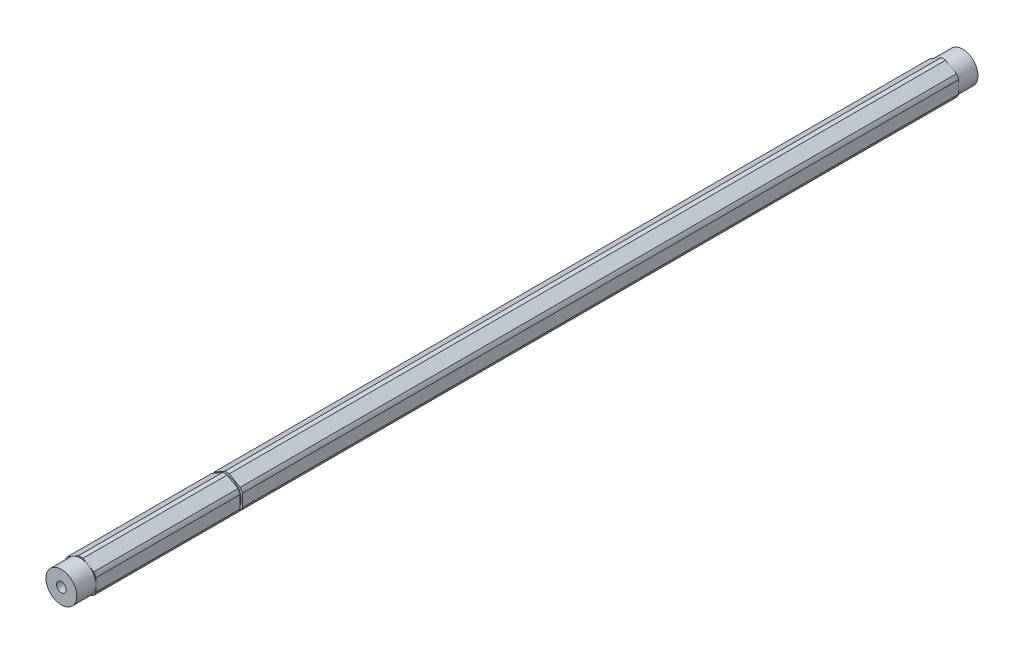
SolidWorks part; units mm, degrees
material "6061-T6 (SS)"
ref_plane "Front Plane" through (0, 0, 0) normal (0, 0, 1) x (1, 0, 0)
ref_plane "Top Plane" through (0, 0, 0) normal (0, 1, 0) x (1, 0, 0)
ref_plane "Right Plane" through (0, 0, 0) normal (1, 0, 0) x (0, 0, -1)
sketch "Sketch1" plane through (0, 0, 0) normal (0, 0, 1) x (1, 0, 0)
  line L1 (0, 7.3323) -> (-6.35, 3.6662)
  line L2 (-6.35, 3.6662) -> (-6.35, -3.6662)
  line L3 (-6.35, -3.6662) -> (0, -7.3323)
  line L4 (0, -7.3323) -> (6.35, -3.6662)
  line L5 (6.35, -3.6662) -> (6.35, 3.6662)
  line L6 (6.35, 3.6662) -> (0, 7.3323)
  circle A0 centre (0, 0) radius 6.35 construction
  circle A1 centre (0, 0) radius 2
  circle A2 centre (0, 0) radius 6.858
  dimension "D1" = 12.7
  dimension "D2" = 4
  dimension "D3" = 13.716
extrude "Boss-Extrude1" add sketch "Sketch1" along normal mid plane 355.6 contours L5 A2 L6 L1 L2 L3 L4 A1
sketch "Sketch3" plane through (0, 0, 177.8) normal (0, 0, 1) x (1, 0, 0)
  circle A0 centre (0, 0) radius 6.35
  circle A1 centre (0, 0) radius 2
  circle A2 centre (0, 0) radius 5.8547 construction
  point P5 (0, 5.8547)
  dimension "D1" = 12.7
  dimension "D2" = 4
  dimension "D3" = 11.7094
extrude "Boss-Extrude3" add sketch "Sketch3" along normal blind 7.9375
mirror "Mirror1" about plane through (0, 0, 0) normal (0, 0, 1) of "Boss-Extrude3"
sketch "Sketch5" plane through (0, 0, 0) normal (1, 0, 0) x (0, 0, -1)
  line L0 (-177.8, 5.8547) -> (-117.475, 5.8547) construction
  line L1 (-118.364, 6.858) -> (-117.475, 6.858)
  line L2 (-118.364, 6.858) -> (-118.364, 5.8547)
  line L3 (-118.364, 5.8547) -> (-117.475, 5.8547)
  line L4 (-117.475, 6.858) -> (-117.475, 5.8547)
  line L5 (-177.8, 5.8547) -> (-177.8, -5.8547) construction
  line L8 (0, 0) -> (14.4053, 0) construction
  dimension "D1" = 0.889
  dimension "D2" = 6.858
  dimension "D3" = 59.436
revolve "Cut-Revolve1" cut sketch "Sketch5" angle 360 about L8
equation "\"D2@Sketch1\"=4mm"
